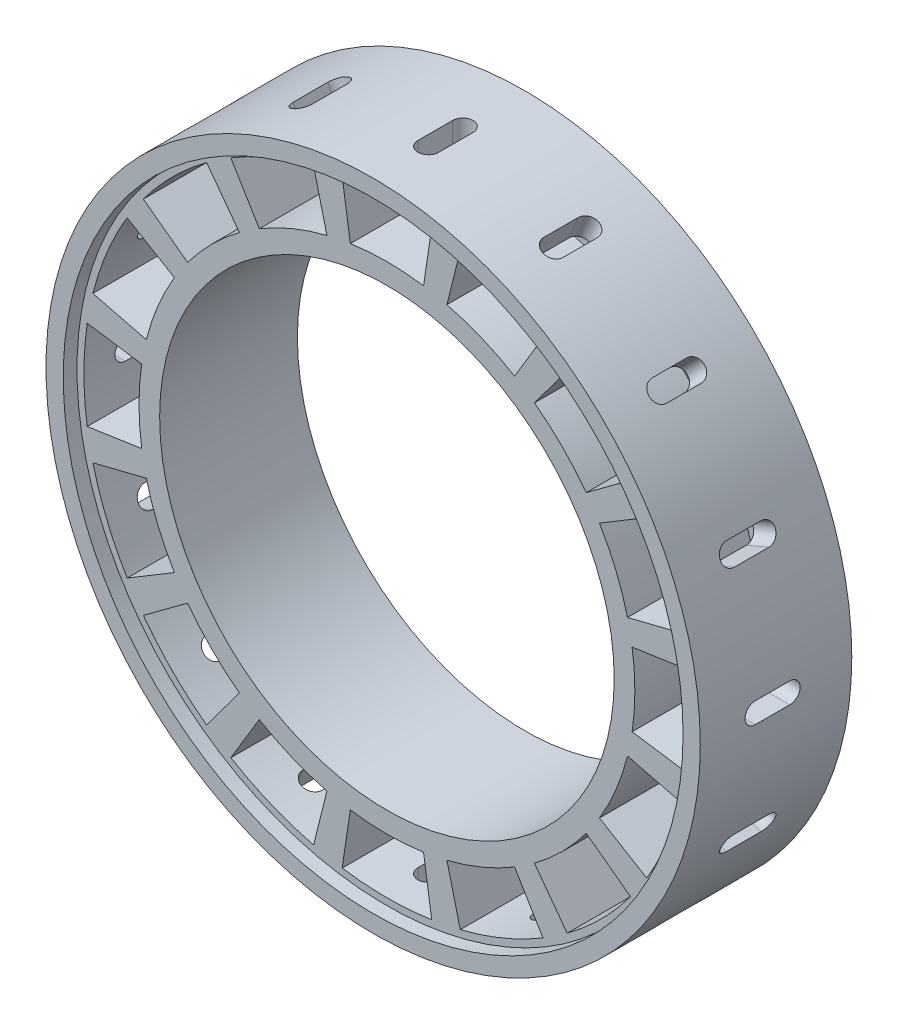
SolidWorks part; units mm, degrees
ref_plane "Front Plane" through (0, 0, 0) normal (0, 0, 1) x (1, 0, 0)
ref_plane "Top Plane" through (0, 0, 0) normal (0, 1, 0) x (1, 0, 0)
ref_plane "Right Plane" through (0, 0, 0) normal (1, 0, 0) x (0, 0, -1)
sketch "Sketch1" plane through (0, 0, 0) normal (0, 0, 1) x (1, 0, 0)
  circle A0 centre (0, 0) radius 33
  circle A1 centre (0, 0) radius 47.5
  dimension "D1" = 66
  dimension "D2" = 95
extrude "Boss-Extrude1" add sketch "Sketch1" along normal blind 2
sketch "Sketch2" plane through (0, 0, 2) normal (0, 0, 1) x (1, 0, 0)
  circle A0 centre (0, 0) radius 33 construction
  circle A1 centre (0, 0) radius 33
  circle A2 centre (0, 0) radius 47.5 construction
  circle A3 centre (0, 0) radius 47.5
  circle A4 centre (0, 0) radius 36
  circle A5 centre (0, 0) radius 44
  circle M1 centre (0, 0) radius 47.5
  circle M2 centre (0, 0) radius 33
  dimension "D1" = 72
  dimension "D2" = 88
extrude "Boss-Extrude2" add sketch "Sketch2" along normal blind 18 contours A4 M2 | A5 M1
ref_plane "Plane1" through (0, 47.5, 0) normal (0, 1, 0) x (1, 0, 0)
sketch "Sketch3" plane through (0, 47.5, 0) normal (0, 1, 0) x (1, 0, 0)
  line L0 (0, -9) -> (0, -14) construction
  line L1 (1.5, -9) -> (1.5, -14)
  line L2 (-1.5, -9) -> (-1.5, -14)
  line L3 (0, -9) -> (0, 0) construction
  arc A0 (1.5, -9) -> (-1.5, -9) centre (0, -9) ccw
  arc A1 (-1.5, -14) -> (1.5, -14) centre (0, -14) ccw
  point P3 (0, -11.5)
  dimension "D2" = 1.5
  dimension "D1" = 5
  dimension "D3" = 9
extrude "Cut-Extrude1" cut sketch "Sketch3" against normal blind 8
sketch "Sketch4" plane through (0, 0, 2) normal (0, 0, 1) x (1, 0, 0)
  line L0 (0, 0) -> (-5.3182, 35.605) construction
  line L1 (-5.3182, 35.605) -> (-6.5, 43.5172)
  line L2 (-6.5, 43.5172) -> (6.5, 43.5172) construction
  line L3 (0, 0) -> (5.3182, 35.605) construction
  line L4 (5.3182, 35.605) -> (6.5, 43.5172)
  line L5 (-8.7686, 43.1174) -> (-7.1743, 35.2779)
  line L6 (8.7686, 43.1174) -> (7.1743, 35.2779)
  line L7 (7.1743, 35.2779) -> (0, 0) construction
  line L8 (0, 0) -> (-7.1743, 35.2779) construction
  circle A0 centre (0, 0) radius 36 construction
  circle A1 centre (0, 0) radius 44 construction
  circle A2 centre (0, 0) radius 44 construction
  circle A3 centre (0, 0) radius 36 construction
  arc A4 (-6.5, 43.5172) -> (-8.7686, 43.1174) centre (0, 0) ccw
  arc A5 (-5.3182, 35.605) -> (-7.1743, 35.2779) centre (0, 0) ccw
  arc A6 (7.1743, 35.2779) -> (5.3182, 35.605) centre (0, 0) ccw
  arc A7 (8.7686, 43.1174) -> (6.5, 43.5172) centre (0, 0) ccw
  dimension "D1" = 13
  dimension "D2" = 3
  dimension "D3" = 3
extrude "Boss-Extrude3" add sketch "Sketch4" along normal blind 18
pattern_circular "CirPattern1" count 16 over 360 about axis through (0, 0, 0) along (0, 0, 1) of "Cut-Extrude1", "Boss-Extrude3"
sketch "Sketch5" plane through (0, 0, 20) normal (0, 0, 1) x (1, 0, 0)
  circle A0 centre (0, 0) radius 47.5 construction
  circle A1 centre (0, 0) radius 47.5
  circle A2 centre (0, 0) radius 45
  dimension "D1" = 90
extrude "Boss-Extrude4" add sketch "Sketch5" along normal blind 2
